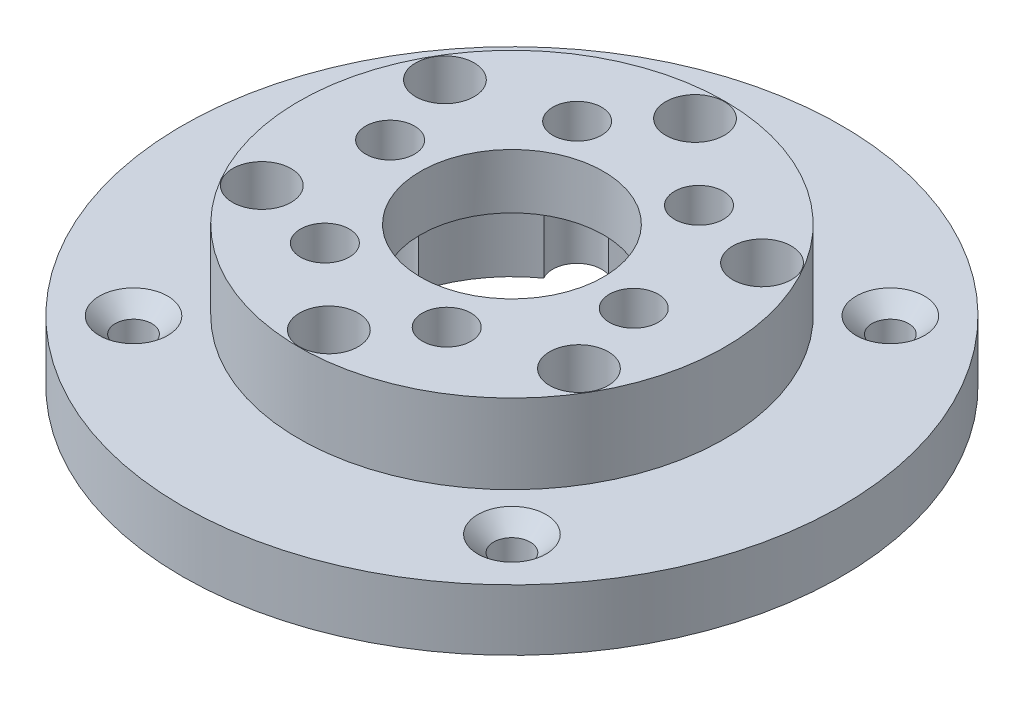
SolidWorks part; units mm, degrees
ref_plane "Front Plane" through (0, 0, 0) normal (0, 0, 1) x (1, 0, 0)
ref_plane "Top Plane" through (0, 0, 0) normal (0, 1, 0) x (1, 0, 0)
ref_plane "Right Plane" through (0, 0, 0) normal (1, 0, 0) x (0, 0, -1)
sketch "Sketch1" plane through (0, 0, 0) normal (0, 1, 0) x (1, 0, 0)
  circle A0 centre (0, 0) radius 27
  dimension "D1" = 54
extrude "Boss-Extrude1" add sketch "Sketch1" along normal blind 5
sketch "Sketch3" plane through (0, 5, 0) normal (0, 1, 0) x (1, 0, 0)
  circle A0 centre (0, 0) radius 17.45
  dimension "D1" = 34.9
extrude "Boss-Extrude2" add sketch "Sketch3" along normal blind 6.5
sketch "Sketch4" plane through (0, 0, 0) normal (0, -1, 0) x (1, 0, 0)
  circle A0 centre (0, 0) radius 11
  dimension "D1" = 22
extrude "Cut-Extrude1" cut sketch "Sketch4" against normal blind 7
sketch "Sketch7" plane through (0, 0, 0) normal (0, -1, 0) x (1, 0, 0)
  line L1 (-15.5, 15.5) -> (15.5, 15.5) construction
  line L2 (-15.5, 15.5) -> (-15.5, -15.5) construction
  line L3 (-15.5, -15.5) -> (15.5, -15.5) construction
  line L4 (15.5, 15.5) -> (15.5, -15.5) construction
  line L5 (-15.5, 15.5) -> (15.5, -15.5) construction
  line L6 (-15.5, -15.5) -> (15.5, 15.5) construction
  circle A0 centre (-15.5, 15.5) radius 1.5
  circle A1 centre (15.5, 15.5) radius 1.5
  circle A2 centre (15.5, -15.5) radius 1.5
  circle A3 centre (-15.5, -15.5) radius 1.5
  point P0 (0, 0)
  dimension "D3" = 3
  dimension "D4" = 3
  dimension "D5" = 3
  dimension "D6" = 3
  dimension "D1" = 31
  dimension "D2" = 31
extrude "Cut-Extrude2" cut sketch "Sketch7" against normal through all
sketch "Sketch8" plane through (0, 11.5, 0) normal (0, 1, 0) x (1, 0, 0)
  circle A0 centre (0, 0) radius 7.5
  dimension "D1" = 15
extrude "Cut-Extrude3" cut sketch "Sketch8" against normal through all
chamfer "Chamfer1" distance 1.3 angle 45 4 edges at (15.5, 5, 17) (15.5, 5, -14) (-15.5, 5, -14) (-15.5, 5, 17)
sketch "Sketch9" plane through (0, 11.5, 0) normal (0, 1, 0) x (1, 0, 0)
  circle A0 centre (0, 0) radius 15 construction
  circle A1 centre (0, 15) radius 2.4
  circle A2 centre (12.9904, 7.5) radius 2.4
  circle A3 centre (12.9904, -7.5) radius 2.4
  circle A4 centre (0, -15) radius 2.4
  circle A5 centre (-12.9904, -7.5) radius 2.4
  circle A6 centre (-12.9904, 7.5) radius 2.4
  point P17 (0, 0)
  dimension "D1" = 30
  dimension "D2" = 4.8
  dimension "D3" = 6
extrude "Cut-Extrude4" cut sketch "Sketch9" against normal blind 15
sketch "Sketch10" plane through (0, 0, 0) normal (0, -1, 0) x (1, 0, 0)
  circle A0 centre (0, 0) radius 11 construction
  circle A1 centre (4.6334, 9.9766) radius 2
  circle A2 centre (10.9566, 0.9757) radius 2
  circle A3 centre (6.3233, -9.0009) radius 2
  circle A4 centre (-4.6334, -9.9766) radius 2
  circle A5 centre (-10.9566, -0.9757) radius 2
  circle A6 centre (-6.3233, 9.0009) radius 2
  point P17 (0, 0)
  dimension "D1" = 6
extrude "Cut-Extrude5" cut sketch "Sketch10" against normal up to next
